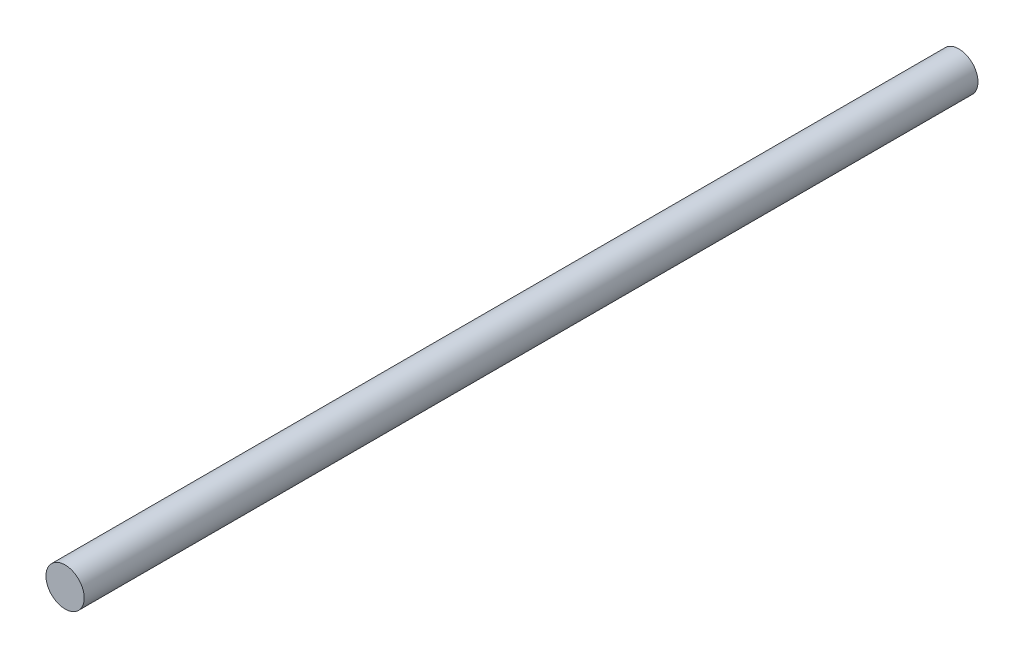
SolidWorks part; units mm, degrees
ref_plane "Спереди" through (0, 0, 0) normal (0, 0, 1) x (1, 0, 0)
ref_plane "Сверху" through (0, 0, 0) normal (0, 1, 0) x (1, 0, 0)
ref_plane "Справа" through (0, 0, 0) normal (1, 0, 0) x (0, 0, -1)
other "Configuration Table"
sketch "Эскиз1" plane through (0, 0, 0) normal (0, 0, 1) x (1, 0, 0)
  circle A0 centre (0, 0) radius 10.7
extrude "Бобышка-Вытянуть2" add sketch "Эскиз1" along normal blind 500
